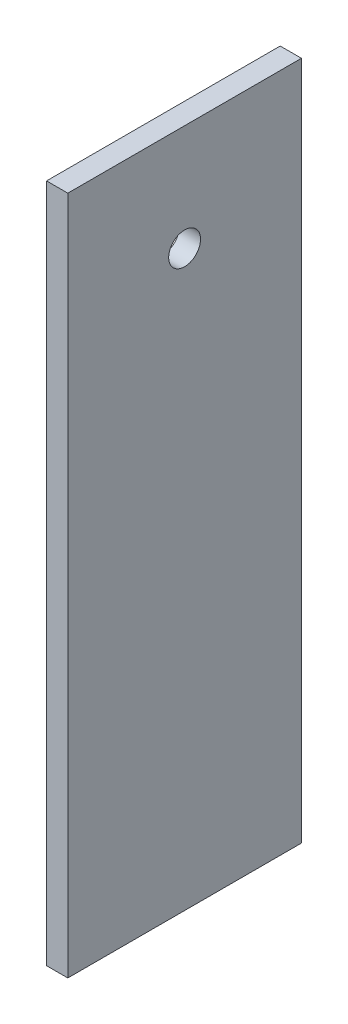
SolidWorks part; units mm, degrees
ref_plane "Alzado" through (0, 0, 0) normal (0, 0, 1) x (1, 0, 0)
ref_plane "Planta" through (0, 0, 0) normal (0, 1, 0) x (1, 0, 0)
ref_plane "Vista lateral" through (0, 0, 0) normal (1, 0, 0) x (0, 0, -1)
sketch "Croquis1" plane through (0, 0, 0) normal (1, 0, 0) x (0, 0, -1)
  line L1 (-275, 800) -> (275, 800)
  line L2 (-275, 800) -> (-275, -800)
  line L3 (-275, -800) -> (275, -800)
  line L4 (275, 800) -> (275, -800)
  line L5 (-275, 800) -> (275, -800) construction
  line L6 (-275, -800) -> (275, 800) construction
  circle A0 centre (0, 550) radius 37.5
  point P0 (0, 0)
  point P8 (0, 0)
  dimension "D3" = 75
  dimension "D1" = 1600
  dimension "D2" = 550
  dimension "D4" = 250
extrude "Saliente-Extruir1" add sketch "Croquis1" along normal blind 50
